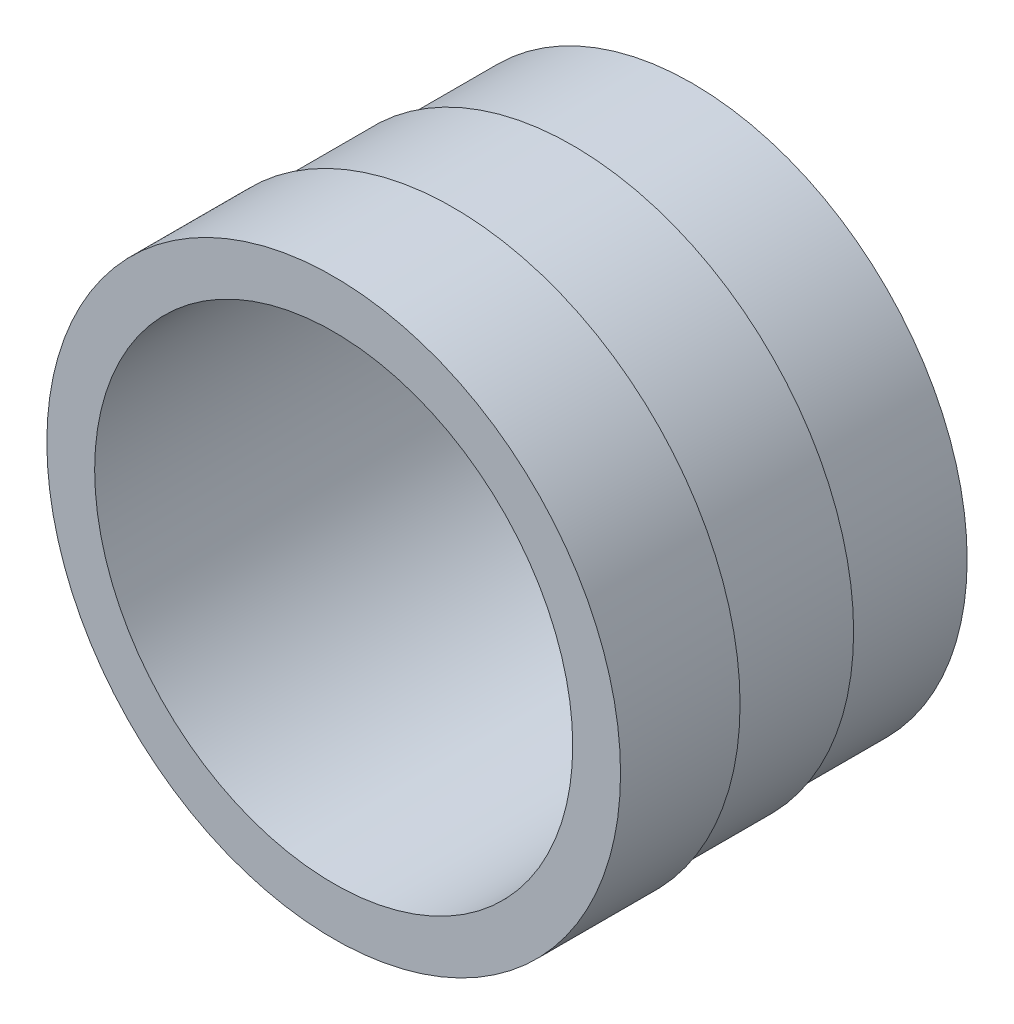
SolidWorks part; units mm, degrees
ref_plane "Front Plane" through (0, 0, 0) normal (0, 0, 1) x (1, 0, 0)
ref_plane "Top Plane" through (0, 0, 0) normal (0, 1, 0) x (1, 0, 0)
ref_plane "Right Plane" through (0, 0, 0) normal (1, 0, 0) x (0, 0, -1)
sketch "Sketch1" plane through (0, 0, 0) normal (0, 1, 0) x (1, 0, 0)
  line L0 (0, 0) -> (0, 38.1)
  line L1 (0, 38.1) -> (-29.21, 38.1)
  line L2 (-29.21, 38.1) -> (-29.21, 25.4)
  line L3 (-29.21, 25.4) -> (-29.845, 25.4)
  line L4 (-29.845, 25.4) -> (-29.845, 12.7)
  line L5 (-29.845, 12.7) -> (-30.48, 12.7)
  line L6 (-30.48, 12.7) -> (-30.48, 0)
  line L7 (-30.48, 0) -> (0, 0)
  dimension "D1" = 12.7
  dimension "D2" = 30.48
  dimension "D3" = 0.635
revolve "Revolve1" add sketch "Sketch1" angle 360 about L0
sketch "Sketch3" plane through (0, 0, -38.1) normal (0, 0, -1) x (-1, 0, 0)
  circle A0 centre (0, 0) radius 25.4
  dimension "D1" = 50.8
extrude "Cut-Extrude2" cut sketch "Sketch3" against normal through all
